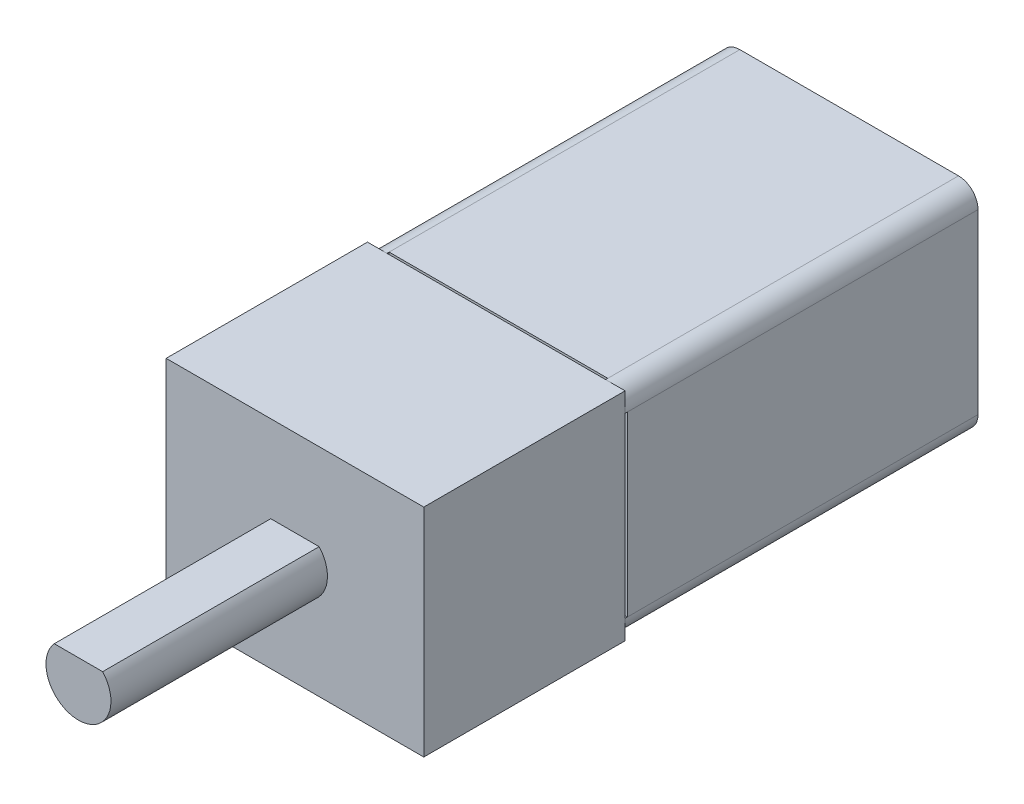
SolidWorks part; units mm, degrees
ref_plane "Alzado" through (0, 0, 0) normal (0, 0, 1) x (1, 0, 0)
ref_plane "Planta" through (0, 0, 0) normal (0, 1, 0) x (1, 0, 0)
ref_plane "Vista lateral" through (0, 0, 0) normal (1, 0, 0) x (0, 0, -1)
sketch "Croquis1" plane through (0, 0, 0) normal (0, 1, 0) x (1, 0, 0)
  line L1 (0, 0) -> (11.9, 0)
  line L2 (0, 0) -> (0, 9.3)
  line L3 (0, 9.3) -> (11.9, 9.3)
  line L4 (11.9, 0) -> (11.9, 9.3)
  dimension "D1" = 9.3
  dimension "D2" = 11.9
extrude "Saliente-Extruir1" add sketch "Croquis1" along normal blind 10
sketch "Croquis2" plane through (0, 0, 0) normal (0, 0, 1) x (1, 0, 0)
  line L0 (5.95, 3.5) -> (5.95, 6) construction
  line L1 (4.832, 6) -> (7.068, 6)
  arc A1 (4.832, 6) -> (7.068, 6) centre (5.95, 5) ccw
  dimension "D1" = 1.5
  dimension "D2" = 2.5
extrude "Saliente-Extruir2" add sketch "Croquis2" along normal blind 10
sketch "Croquis3" plane through (0, 0, -9.3) normal (0, 0, -1) x (-1, 0, 0)
  line L1 (-11, 10) -> (-0.9, 10)
  line L2 (-11.9, 9.1) -> (-11.9, 0.9)
  line L3 (-11, 0) -> (-0.9, 0)
  line L4 (0, 9.1) -> (0, 0.9)
  arc A0 (-11.9, 9.1) -> (-11, 10) centre (-11, 9.1) cw
  arc A1 (0, 9.1) -> (-0.9, 10) centre (-0.9, 9.1) ccw
  arc A2 (-11, 0) -> (-11.9, 0.9) centre (-11, 0.9) cw
  arc A3 (0, 0.9) -> (-0.9, 0) centre (-0.9, 0.9) cw
  point P8 (-11.9, 10)
  point P15 (0, 0)
  dimension "D1" = 0.9
extrude "Saliente-Extruir3" add sketch "Croquis3" along normal blind 16.3
sketch "Croquis6" plane through (0, 10, 0) normal (0, 1, 0) x (1, 0, 0)
  line L0 (11, 25.6) -> (11, 9.3) construction
  line L1 (0.9, 9.3) -> (11, 9.3)
  line L2 (0.9, 9.3) -> (0.9, 9.4)
  line L3 (0.9, 9.4) -> (11, 9.4)
  line L4 (11, 9.3) -> (11, 9.4)
  dimension "D1" = 0.1
extrude "Cortar-Extruir1" cut sketch "Croquis6" against normal blind 0.1
sketch "Croquis7" plane through (11.9, 0, 0) normal (1, 0, 0) x (0, 0, -1)
  line L0 (25.6, 0.9) -> (9.3, 0.9) construction
  line L1 (9.3, 9.1) -> (9.4, 9.1)
  line L2 (9.3, 9.1) -> (9.3, 0.9)
  line L3 (9.3, 0.9) -> (9.4, 0.9)
  line L4 (9.4, 9.1) -> (9.4, 0.9)
  dimension "D1" = 0.1
extrude "Cortar-Extruir2" cut sketch "Croquis7" against normal blind 0.1
sketch "Croquis8" plane through (0, 0, 0) normal (-1, 0, 0) x (0, 0, 1)
  line L0 (-25.6, 9.1) -> (-9.3, 9.1) construction
  line L1 (-9.3, 0.9) -> (-9.4, 0.9)
  line L2 (-9.3, 0.9) -> (-9.3, 9.1)
  line L3 (-9.3, 9.1) -> (-9.4, 9.1)
  line L4 (-9.4, 0.9) -> (-9.4, 9.1)
  dimension "D1" = 0.1
extrude "Cortar-Extruir3" cut sketch "Croquis8" against normal blind 0.1
sketch "Croquis9" plane through (0, 0, 0) normal (0, -1, 0) x (1, 0, 0)
  line L0 (0.9, -25.6) -> (0.9, -9.3) construction
  line L1 (11, -9.3) -> (0.9, -9.3)
  line L2 (11, -9.3) -> (11, -9.4)
  line L3 (11, -9.4) -> (0.9, -9.4)
  line L4 (0.9, -9.3) -> (0.9, -9.4)
  dimension "D1" = 0.1
extrude "Cortar-Extruir4" cut sketch "Croquis9" against normal blind 0.1
